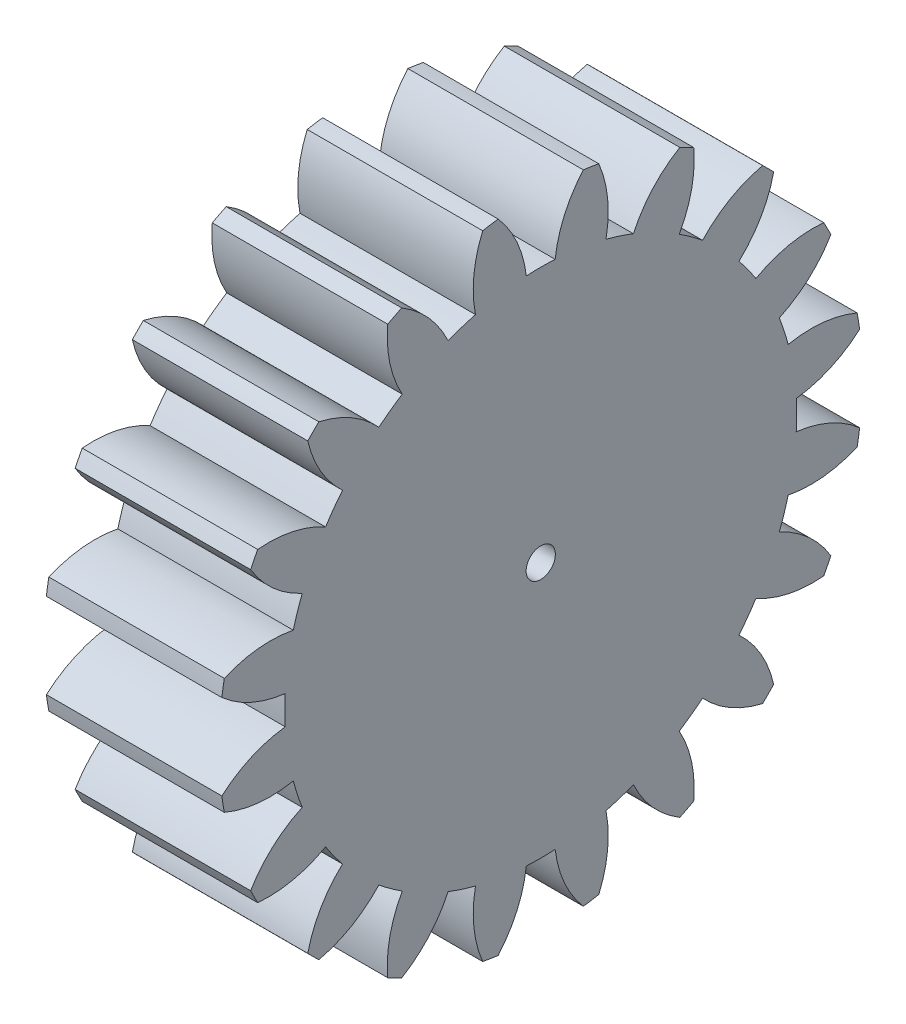
SolidWorks part; units mm, degrees
ref_plane "Plane1" through (0, 0, 0) normal (0, 0, 1) x (1, 0, 0)
ref_plane "Plane2" through (0, 0, 0) normal (0, 1, 0) x (1, 0, 0)
ref_plane "Plane3" through (0, 0, 0) normal (1, 0, 0) x (0, 0, -1)
other "Configuration Table"
sketch "HoldingSke" plane through (0, 0, 0) normal (0, 1, 0) x (1, 0, 0)
  line L0 (0, 0) -> (0.1879, -0.0684)
  line L1 (-15, 0) -> (100, 0) construction
  line L2 (0, 0) -> (-2.1039, 2.3779)
  line L3 (0, 0) -> (-11.863, 4.5341)
  line L4 (0, 0) -> (8.1152, 2.9537)
  line L5 (0, 0) -> (-46.8476, -17.4728)
  line L6 (0, 0) -> (-24.8689, -16.7791)
  line L7 (-2.1039, 2.3779) -> (8.6586, 51.2059)
  line L8 (-76.2, 54.61) -> (-75.3, 54.61)
  line L9 (-71.009, 38.7566) -> (-53.1078, 45.2721)
  line L10 (-76.2, 71.12) -> (104.1128, 71.12)
  line L11 (0, 0) -> (-30, 0)
  line L12 (-76.2, 101.6) -> (-76.033, 101.6)
  line L13 (24.9733, 27.94) -> (52.9518, 28.4284)
  line L14 (24.9733, 27.94) -> (24.9743, 27.94)
  line L15 (24.9733, 27.94) -> (100.4006, 29.5858)
  line L16 (-63.627, -5) -> (-12.827, -5)
  circle A0 centre (0, 0) radius 2.5
  circle A1 centre (0, 0) radius 37.5
  circle A2 centre (0, 0) radius 37.5
  circle A3 centre (0, 0) radius 2.5
  dimension "MHD" = 75
  dimension "Hub_dia" = 75
  dimension "Bore" = 5
  dimension "MBD" = 5
  dimension "Num_teeth" = 20
  dimension "Pitch" = 0.2
  dimension "Overall_len" = 50
  dimension "Show_teeth" = 20
  dimension "Thickness" = 30
  dimension "OAL" = 50.0001
  dimension "T_dim" = 0.9
  dimension "Ap" = 20
  dimension "H" = 19.05
  dimension "Pitch_radius" = 180.3128
  dimension "Width" = 30
  dimension "Backlash" = 0.167
  dimension "Addendum_fac" = 1
  dimension "Dedendum_fac" = 1.25
  dimension "Clearance_fac" = 0.25
  dimension "Dedendum_add" = 0.001
  dimension "Module" = 5
sketch "BasProSke" plane through (0, 0, 0) normal (0, 1, 0) x (1, 0, 0)
  line L0 (-10, 0) -> (60, 0) construction
  line L1 (0, 0) -> (0, 55)
  line L2 (0, 0) -> (30, 0)
  line L3 (30, 0) -> (30, 55)
  line L4 (30, 55) -> (0, 55)
  dimension "Thickness" = 30
  dimension "Diameter" = 110
revolve "Base-Revolve" add sketch "BasProSke" angle 360 about L0
sketch "TooCutSke" plane through (0, 0, 0) normal (1, 0, 0) x (0, 0, -1)
  line L1 (0, 0) -> (0, 107) construction
  line L2 (0, 0) -> (-4.2151, 49.822) construction
  line L3 (0, 0) -> (-15.6021, 98.5081) construction
  line L4 (-4.2151, 49.822) -> (-7.8011, 49.254) construction
  arc A0 (2.4648, 43.6795) -> (-2.4648, 43.6795) centre (0, 0) ccw
  arc A1 (7.3009, 54.5389) -> (-7.3009, 54.5389) centre (0, 0) ccw
  circle A2 centre (0, 0) radius 50 construction
  circle A3 centre (0, 0) radius 46.9846 construction
  arc A4 (-2.4648, 43.6795) -> (-7.3009, 54.5389) centre (-22.3276, 41.3405) ccw
  arc A5 (7.3009, 54.5389) -> (2.4648, 43.6795) centre (22.3276, 41.3405) ccw
  dimension "Root_dia" = 87.498
  dimension "Overcut_dia" = 110.0508
  dimension "Pitch_dia" = 100
  dimension "Base_dia" = 93.9693
  dimension "Flank_rad" = 20
  dimension "Half_ang" = 9
  dimension "Half_CT" = 3.6307
extrude "ToothCut" cut sketch "TooCutSke" along normal through all
fillet "Breaks" [suppressed] radius 0.1
fillet "RootFillets" [suppressed] radius 1.251
pattern_circular "TeethCuts" count 20 every 18 about axis through (-10, 0, 0) along (1, 0, 0) of "ToothCut", "RootFillets", "Breaks"
sketch "HubNeaOneSke" plane through (0, 0, 0) normal (-1, 0, 0) x (0, 0, 1)
  circle A0 centre (0, 0) radius 37.5
  dimension "Diameter" = 75
extrude "HubNearOne" [suppressed] add sketch "HubNeaOneSke" along normal blind 20.0001
sketch "HubNeaBotSke" plane through (0, 0, 0) normal (-1, 0, 0) x (0, 0, 1)
  circle A0 centre (0, 0) radius 37.5
  dimension "Diameter" = 75
extrude "HubNearBoth" [suppressed] add sketch "HubNeaBotSke" along normal blind 10
ref_plane "FarPln" through (30, 0, 0) normal (1, 0, 0) x (0, 0, -1)
sketch "HubFarSke" plane through (30, 0, 0) normal (1, 0, 0) x (0, 0, -1)
  circle A0 centre (0, 0) radius 37.5
  dimension "Diameter" = 75
extrude "HubFar" [suppressed] add sketch "HubFarSke" along normal blind 10
sketch "BorSke" plane through (0, 0, 0) normal (1, 0, 0) x (0, 0, -1)
  circle A0 centre (0, 0) radius 2.5
  dimension "Diameter" = 5
extrude "Bore" cut sketch "BorSke" along normal mid plane 100.0001
sketch "KeySke" plane through (0, 0, 0) normal (1, 0, 0) x (0, 0, -1)
  line L0 (-1, 0) -> (-1, 3.4)
  line L1 (-1, 3.4) -> (1, 3.4)
  line L2 (1, 3.4) -> (1, 0)
  line L3 (0, 0) -> (0, 34) construction
  line L4 (-1, 0) -> (1, 0)
  dimension "Offset" = 3.4
  dimension "Width" = 2
extrude "Keyway" [suppressed] cut sketch "KeySke" along normal mid plane 100.0001
pattern_circular "Keyway2" [suppressed] count 2 every 90 about axis through (-10, 0, 0) along (1, 0, 0)
sketch "草图1" plane through (0, 0, 0) normal (-1, 0, 0) x (0, 0, 1)
  circle A0 centre (0, 0) radius 17.25 construction
  circle A1 centre (0, -17.25) radius 2
  circle A2 centre (-14.9389, -8.625) radius 2
  circle A3 centre (-14.9389, 8.625) radius 2
  circle A4 centre (0, 17.25) radius 2
  circle A5 centre (14.9389, 8.625) radius 2
  circle A6 centre (14.9389, -8.625) radius 2
  point P18 (0, 0)
  dimension "D1" = 34.5
  dimension "D2" = 4
  dimension "D3" = 6
extrude "凸台-拉伸1" add sketch "草图1" along normal blind 10
equation "' \"Module@HoldingSke\" = 6.35"
equation "' \"Num_teeth@HoldingSke\" = 12"
equation "' \"Ap@HoldingSke\" =  20"
equation "' \"Ap@HoldingSke\" = 20"
equation "' \"Width@HoldingSke\" = 0.5 * 25.4"
equation "' \"Hub_dia@HoldingSke\"= 1 * 25.4"
equation "' \"Hub_dia@HoldingSke\" = 1 * 25.4"
equation "' \"Overall_len@HoldingSke\" = 1.0 * 25.4"
equation "' \"Bore@HoldingSke\" = 0.75 * 25.4"
equation "' \"T_dim@HoldingSke\" = 0.1 * 25.4"
equation "' \"Width@KeySke\" = 0.25 * 25.4"
equation "' \"Show_teeth@HoldingSke\" = 13"
equation "' \"Backlash@HoldingSke\" = 0.009 * 25.4"
equation "' \"Addendum_fac@HoldingSke\" = 1.0"
equation "' \"Dedendum_fac@HoldingSke\" = 1.25"
equation "' \"Dedendum_add@HoldingSke\" = 0.00005 * 25.4"
equation "' \"Clearance_fac@HoldingSke\" = 0.25"
equation "\"Pitch@HoldingSke\" = 1 / \"Module@HoldingSke\""
equation "\"Overcut_dia@TooCutSke\" = (\"Num_teeth@HoldingSke\" + 2 * \"Addendum_fac@HoldingSke\") / \"Pitch@HoldingSke\" + 0.002 * 25.4"
equation "\"Pitch_dia@TooCutSke\" = \"Num_teeth@HoldingSke\" / \"Pitch@HoldingSke\""
equation "\"Base_dia@TooCutSke\" = \"Num_teeth@HoldingSke\" / \"Pitch@HoldingSke\" * cos((\"Ap@HoldingSke\"  * 3.14159265 / 180))"
equation "\"Root_dia@TooCutSke\" = (\"Num_teeth@HoldingSke\" + 2) / \"Pitch@HoldingSke\" - 2 * (\"Addendum_fac@HoldingSke\" + \"Dedendum_fac@HoldingSke\") / \"Pitch@HoldingSke\" - \"Dedendum_add@HoldingSke\" * 2"
equation "\"Half_ang@TooCutSke\" = 180 / \"Num_teeth@HoldingSke\""
equation "\"Half_CT@TooCutSke\" = \"Num_teeth@HoldingSke\" / \"Pitch@HoldingSke\" * sin((3.14159265 / 2 / \"Num_teeth@HoldingSke\")) / 2 - 7 * \"Backlash@HoldingSke\" / 4"
equation "\"Flank_rad@TooCutSke\" = \"Num_teeth@HoldingSke\" / \"Pitch@HoldingSke\" / 5"
equation "\"Radius@RootFillets\" = \"Clearance_fac@HoldingSke\" / \"Pitch@HoldingSke\" + \"Dedendum_add@HoldingSke\""
equation "\"Break_rad@Breaks\" = 0.02 / \"Pitch@HoldingSke\""
equation "\"Thickness@HoldingSke\" = \"Width@HoldingSke\""
equation "\"OAL@HoldingSke\" = \"Thickness@HoldingSke\""
equation "\"MHD@HoldingSke\" = (\"Num_teeth@HoldingSke\" + 2) / \"Pitch@HoldingSke\" - 2 * (\"Addendum_fac@HoldingSke\" + \"Dedendum_fac@HoldingSke\")  / \"Pitch@HoldingSke\" - \"Dedendum_add@HoldingSke\" * 2"
equation "\"MBD@HoldingSke\" = (\"Num_teeth@HoldingSke\" + 2) / \"Pitch@HoldingSke\" - 2 * (\"Addendum_fac@HoldingSke\" + \"Dedendum_fac@HoldingSke\")  / \"Pitch@HoldingSke\" - \"Dedendum_add@HoldingSke\" * 2 - 0.002 * 25.4"
equation "\"MHD@HoldingSke\" = ((sgn( \"MHD@HoldingSke\" - \"Hub_dia@HoldingSke\" )-1)*( \"MHD@HoldingSke\" - \"Hub_dia@HoldingSke\" ))/-2+ \"Hub_dia@HoldingSke\""
equation "\"MBD@HoldingSke\" = ((sgn( \"MBD@HoldingSke\" - \"Bore@HoldingSke\" )-1)*( \"MBD@HoldingSke\" - \"Bore@HoldingSke\" ))/-2+ \"Bore@HoldingSke\""
equation "\"OAL@HoldingSke\" = ((sgn( \"OAL@HoldingSke\" - \"Overall_len@HoldingSke\" )+1)*( \"OAL@HoldingSke\" - \"Overall_len@HoldingSke\" ))/2 + \"Overall_len@HoldingSke\" + 0.000002 * 25.4"
equation "\"Num_teeth@TeethCuts\" = int( \"Show_teeth@HoldingSke\" ) + 1"
equation "\"Num_teeth@TeethCuts\" = ((sgn( \"Num_teeth@TeethCuts\" - \"Num_teeth@HoldingSke\" )-1)*( \"Num_teeth@TeethCuts\" - \"Num_teeth@HoldingSke\" ))/-2+ \"Num_teeth@HoldingSke\""
equation "\"Num_teeth@TeethCuts\" = ((sgn( \"Num_teeth@TeethCuts\" - 2.0)+1)*( \"Num_teeth@TeethCuts\" - 2.0))/2 +2.0"
equation "\"Angle@TeethCuts\" = 360.0 / \"Num_teeth@HoldingSke\""
equation "\"Diameter@BasProSke\" = (\"Num_teeth@HoldingSke\" + 2 * \"Addendum_fac@HoldingSke\") / \"Pitch@HoldingSke\""
equation "\"Thickness@BasProSke\"  = \"Thickness@HoldingSke\""
equation "' \"Fillet_rad@BasProSke\" =  \"Thickness@HoldingSke\" * 0.05"
equation "' \"Fillet_rad@BasProSke\" = \"Thickness@HoldingSke\" * 0.05"
equation "\"MHD@HoldingSke\" = ((sgn( \"MHD@HoldingSke\" - \"Root_dia@TooCutSke\" )-1)*( \"MHD@HoldingSke\" - \"Root_dia@TooCutSke\" ))/-2+ \"Root_dia@TooCutSke\""
equation "\"Diameter@HubNeaOneSke\" = \"MHD@HoldingSke\""
equation "\"Length@HubNearOne\" = \"OAL@HoldingSke\" - \"Thickness@BasProSke\""
equation "\"Diameter@HubNeaBotSke\" = \"MHD@HoldingSke\""
equation "\"Length@HubNearBoth\" = ( \"OAL@HoldingSke\" - \"Thickness@BasProSke\" ) / 2.0"
equation "\"Thickness@FarPln\" = \"Thickness@BasProSke\""
equation "\"Diameter@HubFarSke\" = \"MHD@HoldingSke\""
equation "\"Length@HubFar\" = ( \"OAL@HoldingSke\" - \"Thickness@BasProSke\" ) / 2.0"
equation "\"Diameter@BorSke\" = \"MBD@HoldingSke\""
equation "\"D1@Bore\" = \"OAL@HoldingSke\" * 2.0"
equation "\"D1@Keyway\" = \"OAL@HoldingSke\" * 2.0"
equation "\"Offset@KeySke\" = \"T_dim@HoldingSke\" + \"MBD@HoldingSke\" / 2.0"
